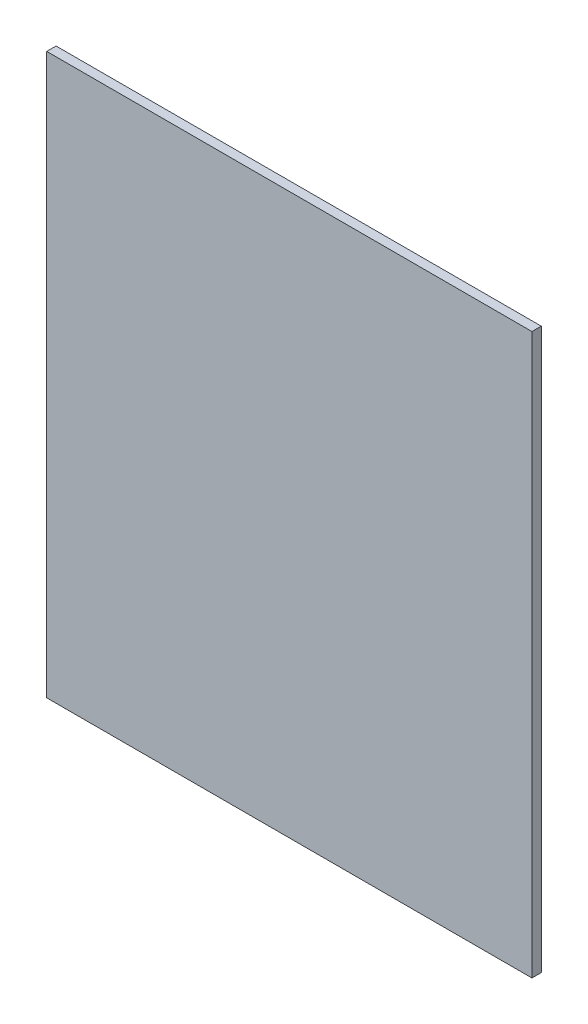
SolidWorks part; units mm, degrees
ref_plane "Plan de face" through (0, 0, 0) normal (0, 0, 1) x (1, 0, 0)
ref_plane "Plan de dessus" through (0, 0, 0) normal (0, 1, 0) x (1, 0, 0)
ref_plane "Plan de droite" through (0, 0, 0) normal (1, 0, 0) x (0, 0, -1)
sketch "Esquisse1" plane through (0, 0, 0) normal (0, 0, 1) x (1, 0, 0)
  line L1 (130, -150) -> (-130, -150)
  line L2 (130, -150) -> (130, 150)
  line L3 (130, 150) -> (-130, 150)
  line L4 (-130, -150) -> (-130, 150)
  line L5 (130, -150) -> (-130, 150) construction
  line L6 (130, 150) -> (-130, -150) construction
  point P0 (0, 0)
  dimension "D1" = 260
  dimension "D2" = 300
extrude "Boss.-Extru.1" add sketch "Esquisse1" along normal blind 5
